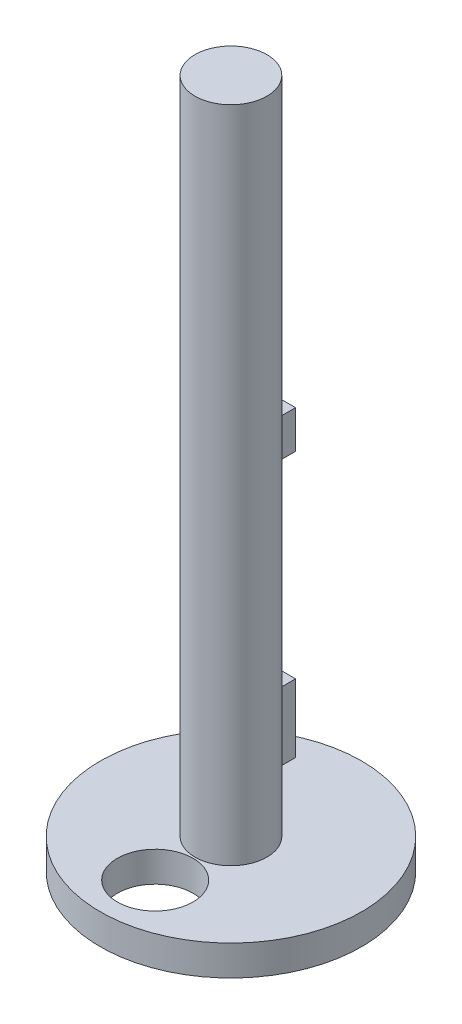
SolidWorks part; units mm, degrees
ref_plane "Front Plane" through (0, 0, 0) normal (0, 0, 1) x (1, 0, 0)
ref_plane "Top Plane" through (0, 0, 0) normal (0, 1, 0) x (1, 0, 0)
ref_plane "Right Plane" through (0, 0, 0) normal (1, 0, 0) x (0, 0, -1)
sketch "Sketch1" plane through (0, 0, 0) normal (0, 1, 0) x (1, 0, 0)
  circle A0 centre (0, 0) radius 4.75
  dimension "D1" = 9.5
extrude "Boss-Extrude1" add sketch "Sketch1" along normal blind 87
sketch "Sketch2" plane through (0, 0, 0) normal (0, -1, 0) x (-1, 0, 0)
  circle A0 centre (0, 0) radius 17.25
  dimension "D1" = 34.5
extrude "Boss-Extrude2" add sketch "Sketch2" along normal blind 4
sketch "Sketch3" plane through (0, -4, 0) normal (0, -1, 0) x (1, 0, 0)
  circle A0 centre (0, 0) radius 10
  circle A1 centre (0, 10) radius 5
  dimension "D1" = 10
  dimension "D2" = 20
extrude "Cut-Extrude1" cut sketch "Sketch3" against normal blind 4 contours A0 A1 | A0 A1
sketch "Sketch4" plane through (0, 0, 0) normal (0, 1, 0) x (1, 0, 0)
  line L1 (-1.75, 0) -> (1.75, 0)
  line L2 (-1.75, 0) -> (-1.75, 6.7777)
  line L3 (-1.75, 6.7777) -> (1.75, 6.7777)
  line L4 (1.75, 0) -> (1.75, 6.7777)
  dimension "D1" = 7
  dimension "D2" = 3.5
  dimension "D3" = 7
extrude "Boss-Extrude3" add sketch "Sketch4" along normal blind 9 from offset 6.5
sketch "Sketch5" plane through (0, 0, 0) normal (0, 1, 0) x (1, 0, 0)
  line L1 (-1.75, 0) -> (1.75, 0)
  line L2 (-1.75, 0) -> (-1.75, 6.7777)
  line L3 (-1.75, 6.7777) -> (1.75, 6.7777)
  line L4 (1.75, 0) -> (1.75, 6.7777)
  dimension "D2" = 3.5
extrude "Boss-Extrude4" add sketch "Sketch5" along normal blind 5 from offset 41.5
